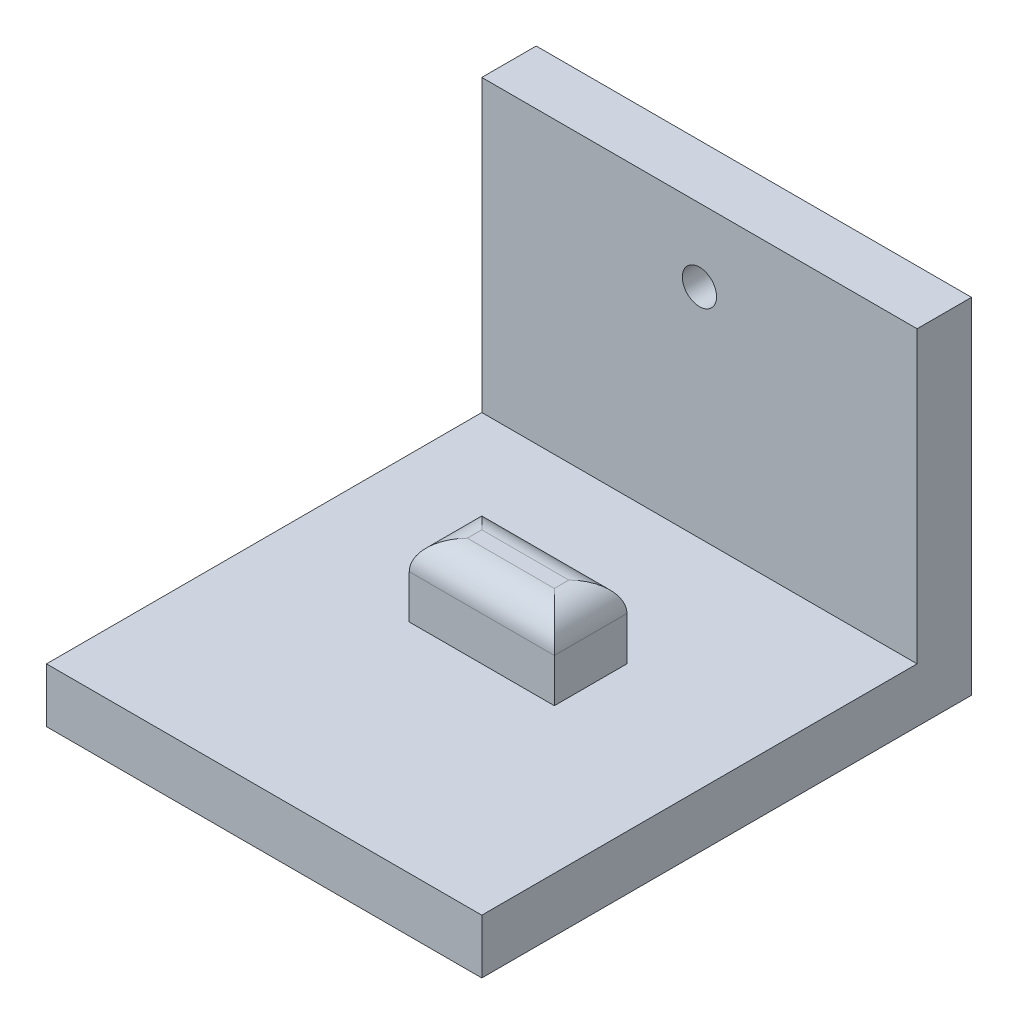
SolidWorks part; units mm, degrees
ref_plane "Front Plane" through (0, 0, 0) normal (0, 0, 1) x (1, 0, 0)
ref_plane "Top Plane" through (0, 0, 0) normal (0, 1, 0) x (1, 0, 0)
ref_plane "Right Plane" through (0, 0, 0) normal (1, 0, 0) x (0, 0, -1)
sketch "Sketch1" plane through (0, 0, 0) normal (1, 0, 0) x (0, 0, -1)
  line L0 (0, 0) -> (-42.8625, 0)
  line L1 (-42.8625, 0) -> (-42.8625, 4.7625)
  line L2 (-42.8625, 4.7625) -> (-4.7625, 4.7625)
  line L3 (-4.7625, 4.7625) -> (-4.7625, 30.1625)
  line L4 (-4.7625, 30.1625) -> (0, 30.1625)
  line L5 (0, 30.1625) -> (0, 0)
  dimension "D1" = 38.1
  dimension "D2" = 25.4
  dimension "D3" = 4.7625
extrude "Boss-Extrude1" add sketch "Sketch1" along normal blind 38.1
sketch "Sketch2" plane through (0, 4.7625, 0) normal (0, 1, 0) x (1, 0, 0)
  line L0 (38.1, -42.8625) -> (0, -42.8625) construction
  line L1 (12.7, -23.8125) -> (25.4, -23.8125)
  line L2 (12.7, -23.8125) -> (12.7, -17.4625)
  line L3 (12.7, -17.4625) -> (25.4, -17.4625)
  line L4 (25.4, -23.8125) -> (25.4, -17.4625)
  line L7 (38.1, -4.7625) -> (0, -4.7625) construction
  point P4 (19.05, -23.8125)
  point P7 (19.05, -42.8625)
  dimension "D1" = 6.35
  dimension "D2" = 12.7
  dimension "D3" = 12.7
extrude "Boss-Extrude2" add sketch "Sketch2" along normal blind 6.35
sketch "Sketch3" plane through (0, 0, 4.7625) normal (0, 0, 1) x (1, 0, 0)
  line L0 (38.1, 30.1625) -> (0, 30.1625) construction
  line L1 (38.1, 4.7625) -> (0, 4.7625) construction
  circle A0 centre (19.05, 23.8125) radius 1.5
  point P5 (19.05, 30.1625)
  dimension "D1" = 3
  dimension "D2" = 19.05
extrude "Cut-Extrude1" cut sketch "Sketch3" against normal through all
fillet "Fillet1" radius 2.54 4 edges at (19.05, 11.1125, 17.4625) (25.4, 11.1125, 20.6375) (19.05, 11.1125, 23.8125) (12.7, 11.1125, 20.6375)
